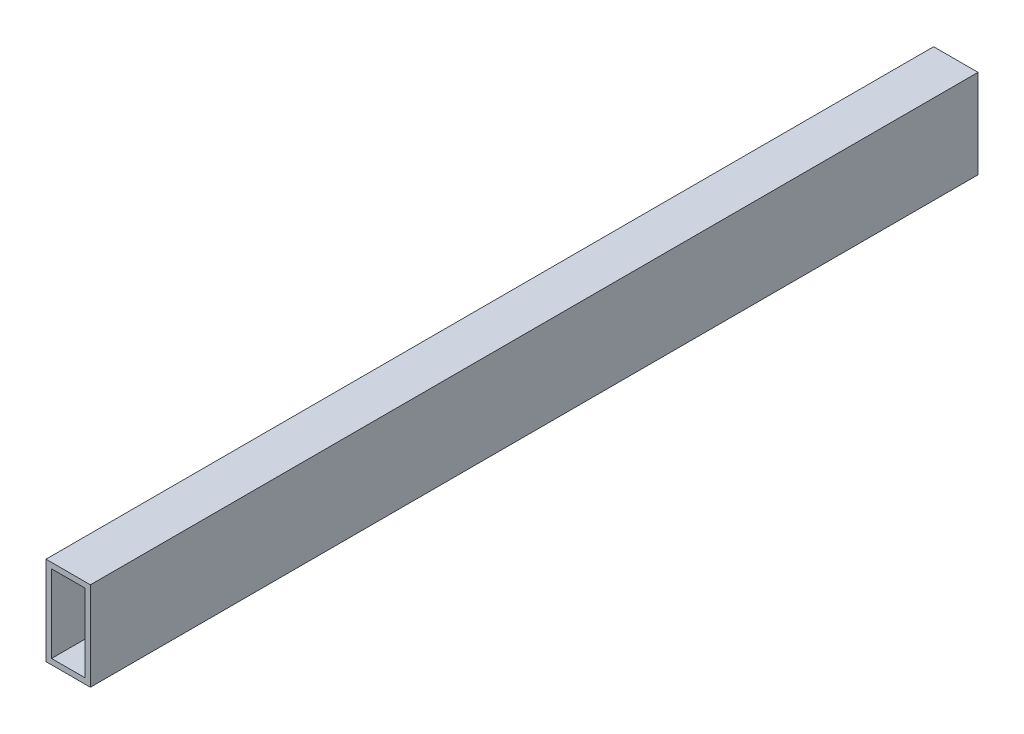
SolidWorks part; units mm, degrees
ref_plane "Front Plane" through (0, 0, 0) normal (0, 0, 1) x (1, 0, 0)
ref_plane "Top Plane" through (0, 0, 0) normal (0, 1, 0) x (1, 0, 0)
ref_plane "Right Plane" through (0, 0, 0) normal (1, 0, 0) x (0, 0, -1)
sketch "Sketch1" plane through (0, 0, 0) normal (0, 0, 1) x (1, 0, 0)
  line L1 (0, 0) -> (-25.4, 0)
  line L2 (0, 0) -> (0, 50.8)
  line L3 (0, 50.8) -> (-25.4, 50.8)
  line L4 (-25.4, 0) -> (-25.4, 50.8)
  line L5 (-3.175, 3.175) -> (-22.225, 3.175)
  line L6 (-3.175, 3.175) -> (-3.175, 47.625)
  line L7 (-3.175, 47.625) -> (-22.225, 47.625)
  line L8 (-22.225, 3.175) -> (-22.225, 47.625)
  dimension "D1" = 25.4
  dimension "D2" = 50.8
  dimension "D3" = 3.175
  dimension "D4" = 3.175
  dimension "D5" = 3.175
  dimension "D6" = 3.175
extrude "Boss-Extrude1" add sketch "Sketch1" along normal blind 508
